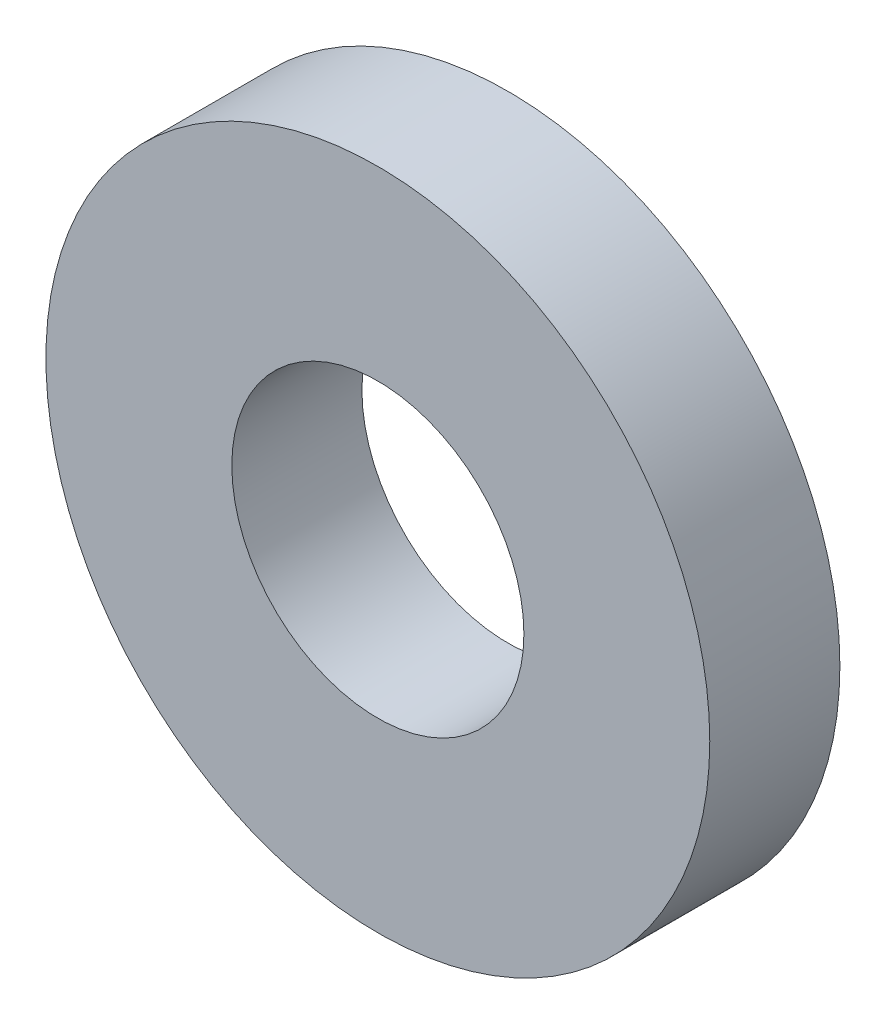
SolidWorks part; units mm, degrees
ref_plane "Front Plane" through (0, 0, 0) normal (0, 0, 1) x (1, 0, 0)
ref_plane "Top Plane" through (0, 0, 0) normal (0, 1, 0) x (1, 0, 0)
ref_plane "Right Plane" through (0, 0, 0) normal (1, 0, 0) x (0, 0, -1)
sketch "Sketch1" plane through (0, 0, 0) normal (0, 0, 1) x (1, 0, 0)
  circle A0 centre (0, 0) radius 7.9375
  circle A1 centre (0, 0) radius 3.4925
  dimension "D1" = 15.875
  dimension "D2" = 6.985
extrude "Boss-Extrude1" add sketch "Sketch1" along normal blind 3.1115
